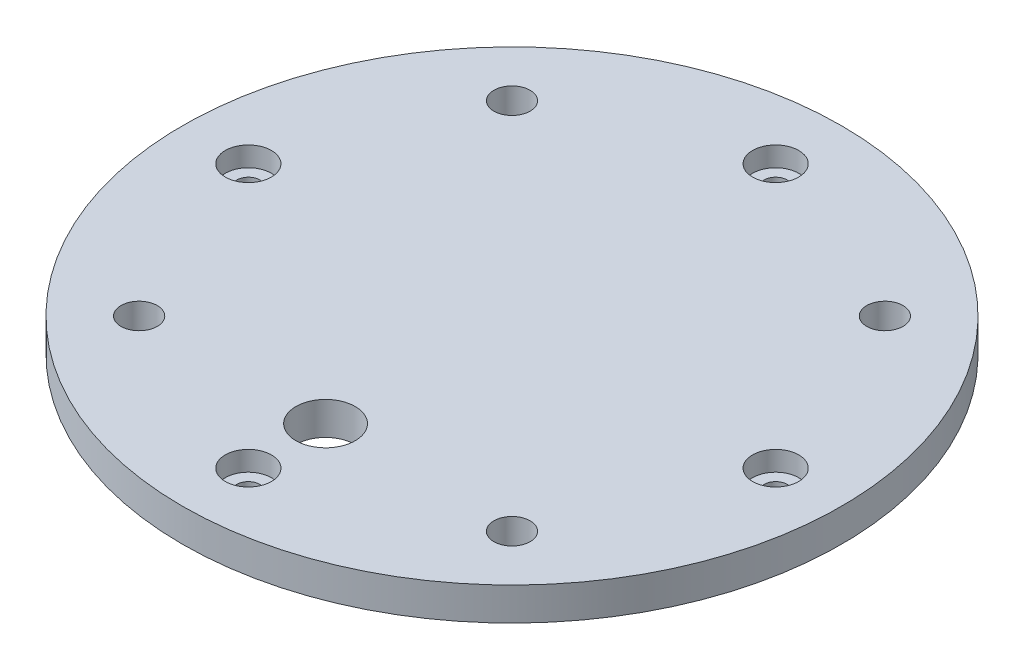
SolidWorks part; units mm, degrees
ref_plane "前视基准面" through (0, 0, 0) normal (0, 0, 1) x (1, 0, 0)
ref_plane "上视基准面" through (0, 0, 0) normal (0, 1, 0) x (1, 0, 0)
ref_plane "右视基准面" through (0, 0, 0) normal (1, 0, 0) x (0, 0, -1)
sketch "草图1" plane through (0, 0, 0) normal (0, 1, 0) x (1, 0, 0)
  circle A0 centre (0, 0) radius 50
  dimension "D1" = 100
extrude "凸台-拉伸1" add sketch "草图1" along normal blind 5
sketch "草图2" plane through (0, 5, 0) normal (0, 1, 0) x (1, 0, 0)
  circle A0 centre (0, 40) radius 1.75
  circle A1 centre (40, 0) radius 1.75
  circle A2 centre (0, -40) radius 1.75
  circle A3 centre (-40, 0) radius 1.75
  point P12 (0, 0)
  dimension "D1" = 3.5
  dimension "D2" = 40
  dimension "D3" = 4
extrude "切除-拉伸1" cut sketch "草图2" against normal blind 12
sketch "草图3" plane through (0, 5, 0) normal (0, 1, 0) x (1, 0, 0)
  line L0 (-45, 40) -> (45, 40) construction
  circle A0 centre (0, 40) radius 3.5
  circle A1 centre (40, 0) radius 3.5
  circle A2 centre (0, -40) radius 3.5
  circle A3 centre (-40, 0) radius 3.5
  point P13 (0, 0)
  dimension "D1" = 7
  dimension "D2" = 4
extrude "切除-拉伸2" cut sketch "草图3" against normal blind 3
sketch "草图4" plane through (0, 5, 0) normal (0, 1, 0) x (1, 0, 0)
  line L0 (0, 0) -> (0, 50000) construction
  line L1 (-45, 40) -> (45, 40) construction
  line L2 (0, 0) -> (28.2843, 28.2843) construction
  circle A0 centre (28.2843, 28.2843) radius 2.75
  circle A1 centre (28.2843, -28.2843) radius 2.75
  circle A2 centre (-28.2843, -28.2843) radius 2.75
  circle A3 centre (-28.2843, 28.2843) radius 2.75
  point P5 (0, 40)
  point P19 (0, 0)
  dimension "D3" = 5.5
  dimension "D1" = 45
  dimension "D2" = 40
  dimension "D4" = 4
extrude "切除-拉伸3" cut sketch "草图4" against normal blind 24
sketch "草图5" plane through (0, 5, 0) normal (0, 1, 0) x (1, 0, 0)
  circle A0 centre (0, -28.2843) radius 4.5
  dimension "D1" = 9
extrude "切除-拉伸4" cut sketch "草图5" against normal blind 16
